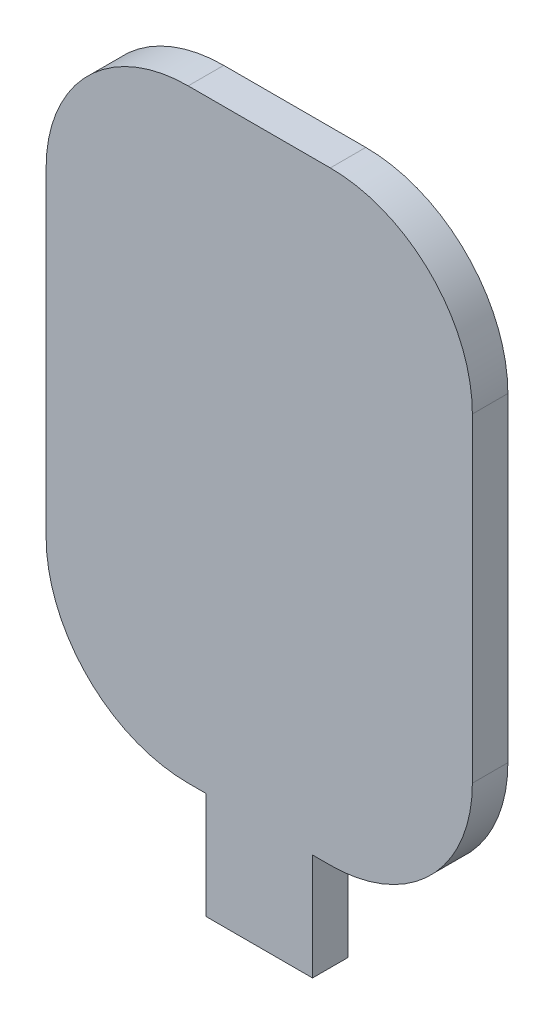
SolidWorks part; units mm, degrees
material "ABS PC"
ref_plane "Front Plane" through (0, 0, 0) normal (0, 0, 1) x (1, 0, 0)
ref_plane "Top Plane" through (0, 0, 0) normal (0, 1, 0) x (1, 0, 0)
ref_plane "Right Plane" through (0, 0, 0) normal (1, 0, 0) x (0, 0, -1)
sketch "Sketch1" plane through (0, 0, 0) normal (0, 0, 1) x (1, 0, 0)
  line L0 (9.525, 9.525) -> (11.1125, 9.525)
  line L1 (0, 0) -> (9.525, 0)
  line L2 (0, 0) -> (0, 9.525)
  line L4 (9.525, 0) -> (9.525, 9.525)
  line L6 (-1.5875, 9.525) -> (0, 9.525)
  line L7 (-14.2875, 22.225) -> (-14.2875, 50.8)
  line L8 (-1.5875, 63.5) -> (11.1125, 63.5)
  line L9 (23.8125, 22.225) -> (23.8125, 50.8)
  arc A0 (-14.2875, 22.225) -> (-1.5875, 9.525) centre (-1.5875, 22.225) ccw
  arc A1 (23.8125, 22.225) -> (11.1125, 9.525) centre (11.1125, 22.225) cw
  arc A2 (11.1125, 63.5) -> (23.8125, 50.8) centre (11.1125, 50.8) cw
  arc A3 (-14.2875, 50.8) -> (-1.5875, 63.5) centre (-1.5875, 50.8) cw
  point P8 (4.7625, 9.525)
  point P12 (-14.2875, 9.525)
  point P15 (23.8125, 9.525)
  point P18 (23.8125, 63.5)
  dimension "D5" = 12.7
  dimension "D1" = 9.525
  dimension "D2" = 9.525
  dimension "D3" = 38.1
  dimension "D4" = 53.975
extrude "Boss-Extrude1" add sketch "Sketch1" along normal blind 3.175
